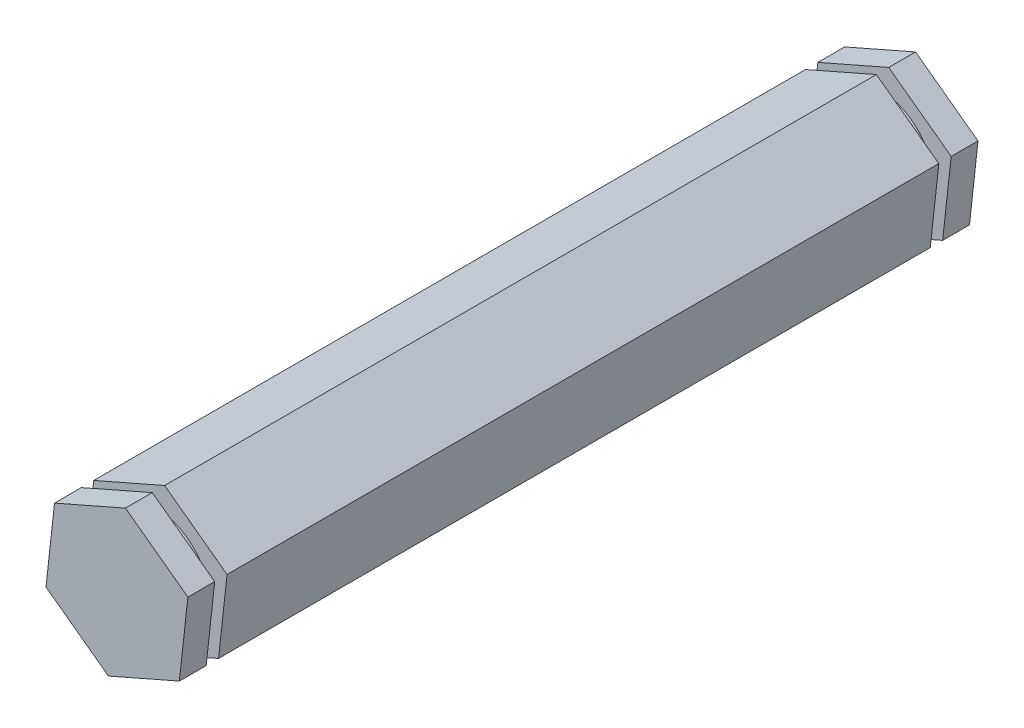
SolidWorks part; units mm, degrees
material "6061 Alloy"
ref_plane "Front Plane" through (0, 0, 0) normal (0, 0, 1) x (1, 0, 0)
ref_plane "Top Plane" through (0, 0, 0) normal (0, 1, 0) x (1, 0, 0)
ref_plane "Right Plane" through (0, 0, 0) normal (1, 0, 0) x (0, 0, -1)
sketch "Sketch1" plane through (0, 0, 0) normal (0, 0, 1) x (1, 0, 0)
  line L1 (5.9083, -4.3422) -> (6.7146, 2.9457)
  line L2 (6.7146, 2.9457) -> (0.8063, 7.2879)
  line L3 (0.8063, 7.2879) -> (-5.9083, 4.3422)
  line L4 (-5.9083, 4.3422) -> (-6.7146, -2.9457)
  line L5 (-6.7146, -2.9457) -> (-0.8063, -7.2879)
  line L6 (-0.8063, -7.2879) -> (5.9083, -4.3422)
  circle A0 centre (0, 0) radius 6.35 construction
  dimension "D1" = 12.7
extrude "Boss-Extrude1" add sketch "Sketch1" along normal blind 67.3735
sketch "Sketch2" plane through (0, 0, 67.3735) normal (0, 0, 1) x (1, 0, 0)
  circle A0 centre (0, 0) radius 5.0292
  dimension "D1" = 10.0584
extrude "Boss-Extrude2" add sketch "Sketch2" along normal blind 1.1684
sketch "Sketch3" plane through (0, 0, 68.5419) normal (0, 0, 1) x (1, 0, 0)
  line L6 (-0.8063, -7.2879) -> (5.9083, -4.3422)
  line L7 (5.9083, -4.3422) -> (6.7146, 2.9457)
  line L8 (6.7146, 2.9457) -> (0.8063, 7.2879)
  line L9 (0.8063, 7.2879) -> (-5.9083, 4.3422)
  line L10 (-5.9083, 4.3422) -> (-6.7146, -2.9457)
  line L11 (-6.7146, -2.9457) -> (-0.8063, -7.2879)
  line L12 (-0.8063, -7.2879) -> (5.9083, -4.3422)
  line L13 (5.9083, -4.3422) -> (6.7146, 2.9457)
  line L14 (6.7146, 2.9457) -> (0.8063, 7.2879)
  line L15 (0.8063, 7.2879) -> (-5.9083, 4.3422)
  line L16 (-5.9083, 4.3422) -> (-6.7146, -2.9457)
  line L17 (-6.7146, -2.9457) -> (-0.8063, -7.2879)
  dimension "D1" = 0
extrude "Boss-Extrude3" add sketch "Sketch3" along normal blind 2.54
sketch "Sketch4" plane through (0, 0, 0) normal (0, 0, -1) x (-1, 0, 0)
  circle A0 centre (0, 0) radius 5.0292
  dimension "D1" = 10.0584
ref_plane "Plane1" through (6.7146, 2.9457, 0) normal (0, 0, -1) x (-1, 0, 0)
sketch "Sketch5" plane through (0, 0, 0) normal (0, 0, -1) x (-1, 0, 0)
  circle A1 centre (0, 0) radius 5.0292
  dimension "D1" = 10.0584
extrude "Boss-Extrude4" add sketch "Sketch5" along normal blind 1.1684
sketch "Sketch6" plane through (0, 0, -1.1684) normal (0, 0, -1) x (-1, 0, 0)
  line L6 (-5.9083, -4.3422) -> (0.8063, -7.2879)
  line L7 (0.8063, -7.2879) -> (6.7146, -2.9457)
  line L8 (6.7146, -2.9457) -> (5.9083, 4.3422)
  line L9 (5.9083, 4.3422) -> (-0.8063, 7.2879)
  line L10 (-0.8063, 7.2879) -> (-6.7146, 2.9457)
  line L11 (-6.7146, 2.9457) -> (-5.9083, -4.3422)
  line L12 (-5.9083, -4.3422) -> (0.8063, -7.2879)
  line L13 (0.8063, -7.2879) -> (6.7146, -2.9457)
  line L14 (6.7146, -2.9457) -> (5.9083, 4.3422)
  line L15 (5.9083, 4.3422) -> (-0.8063, 7.2879)
  line L16 (-0.8063, 7.2879) -> (-6.7146, 2.9457)
  line L17 (-6.7146, 2.9457) -> (-5.9083, -4.3422)
  dimension "D1" = 0
extrude "Boss-Extrude5" add sketch "Sketch6" along normal blind 2.54
